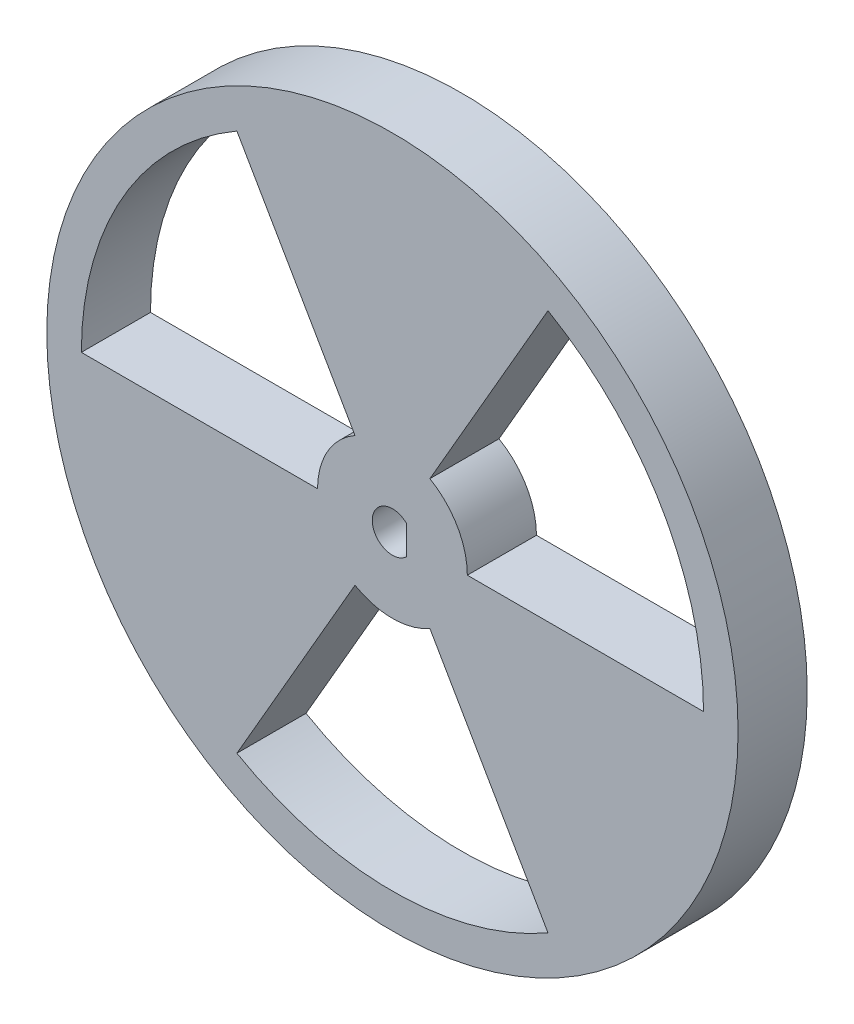
SolidWorks part; units mm, degrees
ref_plane "Plan de face" through (0, 0, 0) normal (0, 0, 1) x (1, 0, 0)
ref_plane "Plan de dessus" through (0, 0, 0) normal (0, 1, 0) x (1, 0, 0)
ref_plane "Plan de droite" through (0, 0, 0) normal (1, 0, 0) x (0, 0, -1)
sketch "Esquisse1" plane through (0, 0, 0) normal (0, 0, 1) x (1, 0, 0)
  line L0 (-54, 0) -> (54, 0)
  line L1 (0, 54) -> (0, -54) construction
  line L2 (-27, 0) -> (-27, 46.7654) construction
  line L3 (-27, 46.7654) -> (0, 0)
  line L4 (27, 0) -> (27, 46.7654) construction
  line L5 (27, 46.7654) -> (0, 0)
  line L6 (-27, 0) -> (-27, -46.7654) construction
  line L7 (-27, -46.7654) -> (0, 0)
  line L8 (27, 0) -> (27, -46.7654) construction
  line L9 (0, 0) -> (27, -46.7654)
  circle A0 centre (0, 0) radius 60
  circle A1 centre (0, 0) radius 54
  circle A3 centre (0, 0) radius 13
  point P8 (-27, 0)
  point P10 (27, 0)
  point P11 (0, -27)
  dimension "D1" = 6
  dimension "D2" = 120
  dimension "D3" = 27
  dimension "D4" = 27
  dimension "D5" = 27
extrude "Boss.-Extru.1" add sketch "Esquisse1" along normal blind 12 contours A0 A1 | A3 L0 A1 L7 | A3 L5 A1 L3 | A3 L9 A1 L0
sketch "Sketch1" plane through (0, 0, 12) normal (0, 0, 1) x (1, 0, 0)
  line L0 (2.4495, 2.5) -> (2.4495, -2.5)
  arc A1 (2.4495, 2.5) -> (2.4495, -2.5) centre (0, 0) ccw
  dimension "D1" = 3.5
  dimension "D2" = 5
extrude "Cut-Extrude1" cut sketch "Sketch1" against normal up to surface (12 mm away) up to face at (27.0684, 15.628, 0)
